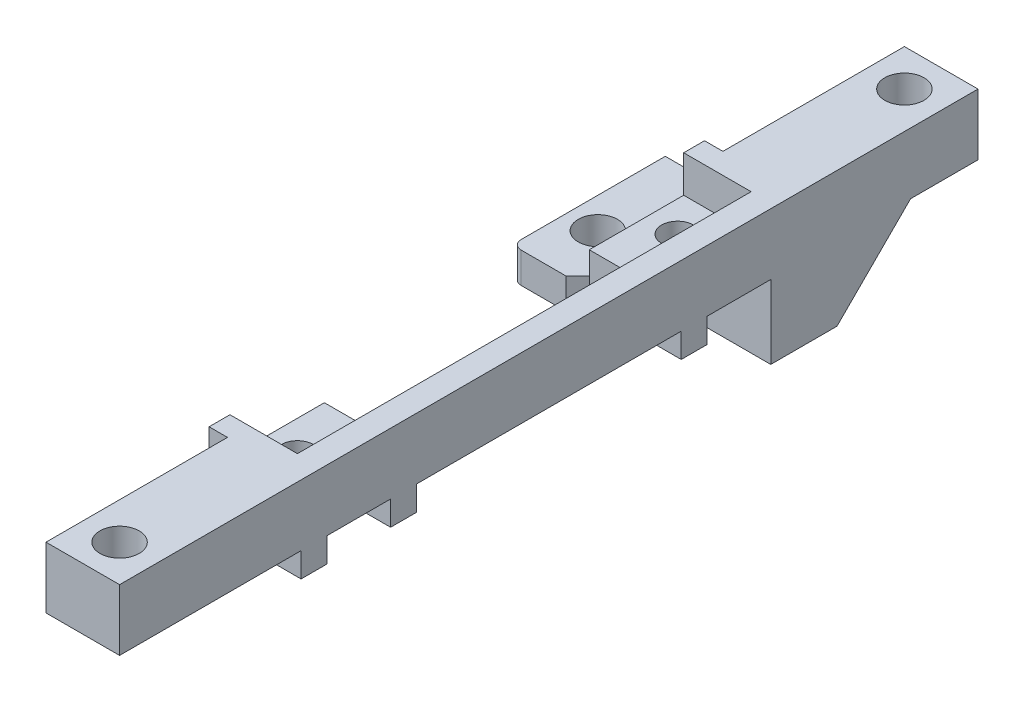
SolidWorks part; units mm, degrees
ref_plane "Front Plane" through (0, 0, 0) normal (0, 0, 1) x (1, 0, 0)
ref_plane "Top Plane" through (0, 0, 0) normal (0, 1, 0) x (1, 0, 0)
ref_plane "Right Plane" through (0, 0, 0) normal (1, 0, 0) x (0, 0, -1)
sketch "Sketch1" plane through (0, 0, 0) normal (0, 1, 0) x (1, 0, 0)
  line L1 (-3, 35) -> (3, 35)
  line L2 (-3, 35) -> (-3, -35)
  line L3 (-3, -35) -> (3, -35)
  line L4 (3, 35) -> (3, -35)
  line L5 (-3, 35) -> (3, -35) construction
  line L6 (-3, -35) -> (3, 35) construction
  point P0 (0, 0)
  dimension "D1" = 70
  dimension "D2" = 6
extrude "Boss-Extrude1" add sketch "Sketch1" along normal blind 5
sketch "Sketch2" plane through (0, 5, 0) normal (0, 1, 0) x (1, 0, 0)
  line L0 (0, -32) -> (0, 32) construction
  line L1 (0, 0) -> (3, 0) construction
  line L2 (3, -35) -> (3, 35) construction
  circle A0 centre (0, -32) radius 1.6
  circle A1 centre (0, 32) radius 1.6
  dimension "D1" = 3.2
  dimension "D2" = 64
extrude "Cut-Extrude1" cut sketch "Sketch2" against normal through all
sketch "Sketch5" plane through (0, 5, 0) normal (0, 1, 0) x (1, 0, 0)
  line L1 (-3, -20.2) -> (-4.5, -20.2)
  line L2 (-3, -20.2) -> (-3, 20.2)
  line L3 (-3, 20.2) -> (-4.5, 20.2)
  line L4 (-4.5, -20.2) -> (-4.5, 20.2)
  line L5 (-3, -20.2) -> (-4.5, 20.2) construction
  line L6 (-3, 20.2) -> (-4.5, -20.2) construction
  line L7 (-3, 35) -> (-3, -35) construction
  line L8 (-3.75, 0) -> (0, 0) construction
  line L9 (3, -35) -> (3, 35) construction
  point P0 (-3.75, 0)
  dimension "D1" = 40.4
  dimension "D2" = 7.5
extrude "Boss-Extrude2" add sketch "Sketch5" against normal up to surface (5 mm away) up to face at (0, 0, -30.4)
sketch "Sketch7" plane through (0, 5, 0) normal (0, 1, 0) x (1, 0, 0)
  line L1 (-13.8896, -18.5) -> (1, -18.5)
  line L2 (-13.8896, -18.5) -> (-13.8896, 18.5)
  line L3 (-13.8896, 18.5) -> (1, 18.5)
  line L4 (1, -18.5) -> (1, 18.5)
  line L5 (-13.8896, -18.5) -> (1, 18.5) construction
  line L6 (-13.8896, 18.5) -> (1, -18.5) construction
  line L8 (3, -35) -> (3, 35) construction
  line L9 (-6.4448, 0) -> (3, 0) construction
  point P0 (-6.4448, 0)
  dimension "D1" = 2
  dimension "D2" = 37
extrude "Cut-Extrude5" cut sketch "Sketch7" against normal blind 3
sketch "Sketch8" plane through (0, 2, 0) normal (0, 1, 0) x (1, 0, 0)
  line L0 (-4.5, 18.5) -> (-4.5, -18.5) construction
  line L1 (-0.5, -10.8) -> (-4.5, -10.8)
  line L2 (-0.5, -10.8) -> (-0.5, 10.8)
  line L3 (-0.5, 10.8) -> (-4.5, 10.8)
  line L4 (-4.5, -10.8) -> (-4.5, 10.8)
  line L5 (-0.5, -10.8) -> (-4.5, 10.8) construction
  line L6 (-0.5, 10.8) -> (-4.5, -10.8) construction
  line L7 (0, 0) -> (-2.5, 0) construction
  point P0 (-2.5, 0)
  dimension "D1" = 4
  dimension "D2" = 21.6
extrude "Cut-Extrude6" cut sketch "Sketch8" against normal blind 3
sketch "Sketch9" plane through (0, 0, 0) normal (0, -1, 0) x (1, 0, 0)
  line L0 (1, -18.5) -> (-4.5, -18.5) construction
  line L1 (3, -23.5) -> (-13.5, -23.5)
  line L2 (3, -23.5) -> (3, -13.5)
  line L3 (3, -13.5) -> (-13.5, -13.5)
  line L4 (-13.5, -23.5) -> (-13.5, -13.5)
  line L5 (3, -23.5) -> (-13.5, -13.5) construction
  line L6 (3, -13.5) -> (-13.5, -23.5) construction
  line L7 (3, 35) -> (3, -35) construction
  circle A0 centre (0, -32) radius 1.6 construction
  point P0 (-5.25, -18.5)
  dimension "D1" = 13.5
  dimension "D2" = 10
  dimension "D3" = 5
extrude "Boss-Extrude3" add sketch "Sketch9" along normal offset from surface (6 mm away) 8 up to face at (-2.125, 2, 0)
sketch "Sketch6" plane through (0, 5, 0) normal (0, 1, 0) x (1, 0, 0)
  line L0 (-2, -15.5) -> (-2, 15.5) construction
  line L1 (0, 0) -> (-2, 0) construction
  line L2 (3, -35) -> (3, 35) construction
  circle A0 centre (-2, 15.5) radius 1.3
  circle A1 centre (-2, -15.5) radius 1.3
  dimension "D2" = 2.6
  dimension "D1" = 31
  dimension "D3" = 5
extrude "Cut-Extrude4" cut sketch "Sketch6" against normal through all
sketch "Sketch10" plane through (0, 0, 0) normal (0, 1, 0) x (1, 0, 0)
  circle A0 centre (-11, 18) radius 1.6
  circle A1 centre (-2, 15.5) radius 1.3 construction
  dimension "D1" = 3.2
  dimension "D3" = 9
  dimension "D2" = 2.5
extrude "Cut-Extrude7" cut sketch "Sketch10" against normal blind 9
sketch "Sketch11" plane through (0, 0, 0) normal (0, 1, 0) x (1, 0, 0)
  line L5 (-13.5, 13.5) -> (-4.5, 13.5)
  line L6 (-4.5, 13.5) -> (-4.5, 20.2)
  line L7 (-3, 20.2) -> (-3, 23.5)
  line L8 (-3, 23.5) -> (-13.5, 23.5)
  line L9 (-13.5, 23.5) -> (-13.5, 13.5)
  line L10 (-13.5, 13.5) -> (-4.5, 13.5)
  line L11 (-4.5, 13.5) -> (-4.5, 20.2)
  line L12 (-3, 20.2) -> (-3, 23.5)
  line L13 (-3, 23.5) -> (-13.5, 23.5)
  line L14 (-13.5, 23.5) -> (-13.5, 13.5)
  line L16 (-4.5, 20.2) -> (-3, 20.2)
  line L17 (-4.5, 20.2) -> (-3, 20.2)
  dimension "D1" = 0
extrude "Cut-Extrude8" cut sketch "Sketch11" against normal offset from surface (3.5 mm away) 2.5 up to face at (-11, -6, -19.6)
sketch "Sketch12" plane through (0, 0, -10.8) normal (0, 0, 1) x (1, 0, 0)
  line L0 (-13.5, -3.5) -> (-4.5, -3.5) construction
  line L1 (-5.0105, -3.5) -> (5.4424, -3.5)
  line L2 (-5.0105, -3.5) -> (-5.0105, 0)
  line L3 (-5.0105, 0) -> (5.4424, 0)
  line L4 (5.4424, -3.5) -> (5.4424, 0)
  line L5 (-5.0105, -3.5) -> (5.4424, 0) construction
  line L6 (-5.0105, 0) -> (5.4424, -3.5) construction
  line L9 (3, 0) -> (-4.5, 0) construction
  point P0 (0.2159, -1.75)
extrude "Cut-Extrude9" [suppressed] cut sketch "Sketch12" against normal blind 8.1
sketch "Sketch13" plane through (3, 0, 0) normal (1, 0, 0) x (0, 0, -1)
  line L0 (23.5, -6) -> (29.5, 0)
  line L1 (23.5, 0) -> (35, 0) construction
  line L2 (29.5, 0) -> (23.5, 0)
  line L3 (23.5, 0) -> (23.5, -6)
extrude "Boss-Extrude4" add sketch "Sketch13" against normal up to surface (6 mm away) up to face at (-3, 1.875, 23.9)
sketch "Sketch14" plane through (0, -6, 0) normal (0, -1, 0) x (1, 0, 0)
  line L0 (3, -13.5) -> (-13.5, -13.5) construction
  line L1 (-4.5, -18.1) -> (5.1956, -18.1)
  line L2 (-4.5, -18.1) -> (-9.1, -13.5)
  line L3 (-9.1, -13.5) -> (5.1956, -13.5)
  line L4 (5.1956, -18.1) -> (5.1956, -13.5)
  line L5 (-4.5, -18.1) -> (5.1956, -13.5) construction
  line L6 (-9.1, -13.5) -> (5.1956, -18.1) construction
  line L13 (-4.5, -10.8) -> (-4.5, -13.5) construction
  point P0 (-0.5817, -16.241)
  dimension "D1" = 45
  dimension "D2" = 4.6
extrude "Cut-Extrude10" cut sketch "Sketch14" against normal up to surface (6 mm away) up to face at (-2, 0, 16.8)
sketch "Sketch15" plane through (-3, 0, 0) normal (-1, 0, 0) x (0, 0, 1)
  line L0 (-23.5, -3.5) -> (-23.5, -6)
  line L1 (-23.5, -6) -> (-26, -3.5)
  line L2 (-29.5, 0) -> (-23.5, -6) construction
  line L3 (-26, -3.5) -> (-23.5, -3.5)
extrude "Boss-Extrude5" add sketch "Sketch15" along normal up to surface (10.5 mm away) up to face at (-13.5, -4.75, -18.5)
fillet "Fillet3" radius 0.75 1 edges at (-13.5, -4.75, -13.5)
sketch "Sketch16" plane through (0, 0, 0) normal (0, -1, 0) x (1, 0, 0)
  line L0 (3, 35) -> (3, -18.1) construction
  line L1 (3, -20.2) -> (-4.5, -20.2)
  line L2 (3, -20.2) -> (3, -18.1)
  line L3 (3, -18.1) -> (-4.5, -18.1)
  line L4 (-4.5, -20.2) -> (-4.5, -18.1)
  line L5 (3, -20.2) -> (-4.5, -18.1) construction
  line L6 (3, -18.1) -> (-4.5, -20.2) construction
  line L8 (-4.5, -10.8) -> (-4.5, -18.1) construction
  line L9 (3, -10.8) -> (-4.5, -10.8)
  line L10 (3, -10.8) -> (3, -12.9)
  line L11 (3, -12.9) -> (-4.5, -12.9)
  line L12 (-4.5, -10.8) -> (-4.5, -12.9)
  line L13 (3, -10.8) -> (-4.5, -12.9) construction
  line L14 (3, -12.9) -> (-4.5, -10.8) construction
  line L15 (3, 12.9) -> (-4.5, 12.9)
  line L16 (3, 12.9) -> (3, 10.8)
  line L17 (3, 10.8) -> (-4.5, 10.8)
  line L18 (-4.5, 12.9) -> (-4.5, 10.8)
  line L19 (3, 12.9) -> (-4.5, 10.8) construction
  line L20 (3, 10.8) -> (-4.5, 12.9) construction
  line L21 (3, 20.2) -> (-4.5, 20.2)
  line L22 (3, 20.2) -> (3, 18.1)
  line L23 (3, 18.1) -> (-4.5, 18.1)
  line L24 (-4.5, 20.2) -> (-4.5, 18.1)
  line L25 (3, 20.2) -> (-4.5, 18.1) construction
  line L26 (3, 18.1) -> (-4.5, 20.2) construction
  circle A0 centre (-2, -15.5) radius 1.3 construction
  circle A1 centre (-2, 15.5) radius 1.3 construction
  point P0 (-0.75, -19.15)
  point P11 (-0.75, -11.85)
  point P16 (-0.75, 11.85)
  point P21 (-0.75, 19.15)
  dimension "D1" = 2.6
  dimension "D2" = 2.1
  dimension "D3" = 2.6
  dimension "D4" = 2.6
  dimension "D5" = 2.6
extrude "Boss-Extrude6" add sketch "Sketch16" along normal blind 2
